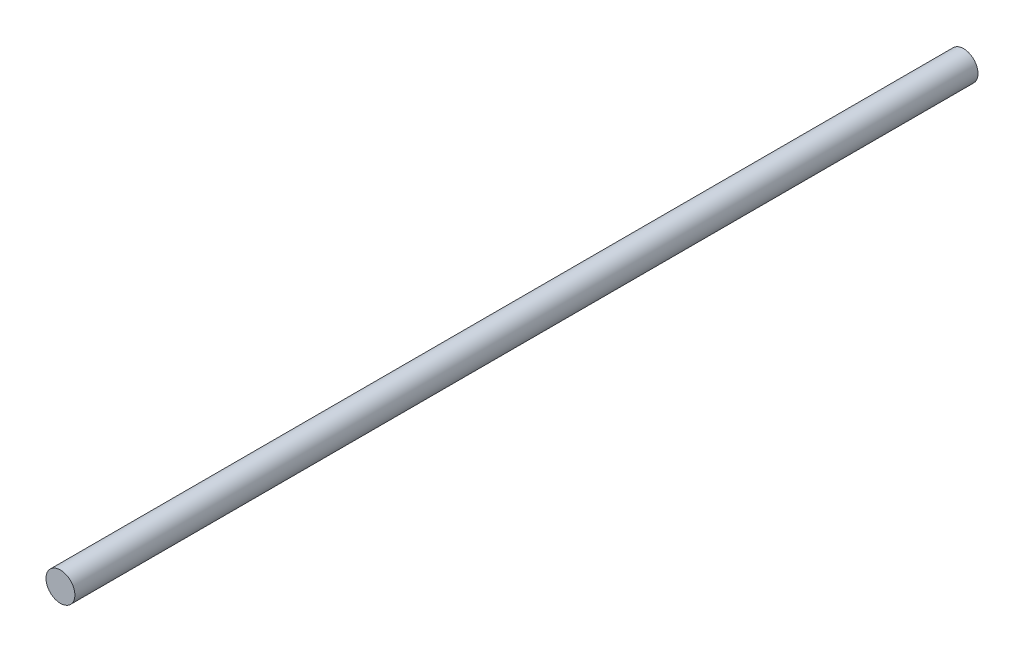
SolidWorks part; units mm, degrees
ref_plane "Спереди" through (0, 0, 0) normal (0, 0, 1) x (1, 0, 0)
ref_plane "Сверху" through (0, 0, 0) normal (0, 1, 0) x (1, 0, 0)
ref_plane "Справа" through (0, 0, 0) normal (1, 0, 0) x (0, 0, -1)
sketch "Эскиз1" plane through (0, 0, 0) normal (0, 0, 1) x (1, 0, 0)
  circle A0 centre (0, 0) radius 4
  dimension "D1" = 8
extrude "Бобышка-Вытянуть1" add sketch "Эскиз1" along normal blind 250
equation "\"RailLenght\"= 150мм"
